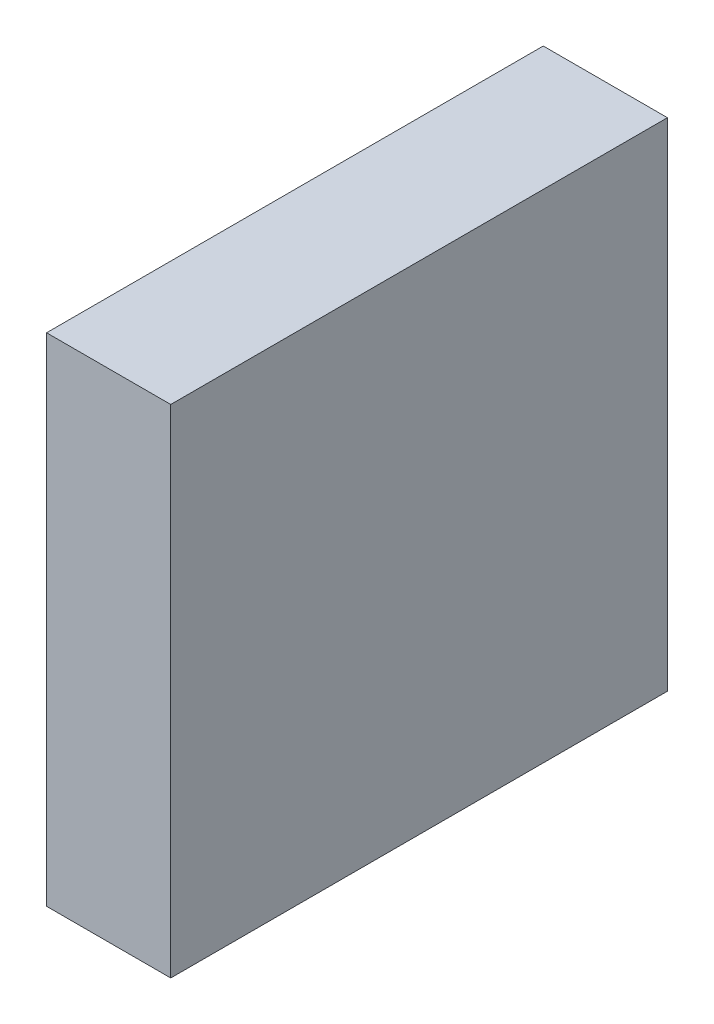
SolidWorks part; units mm, degrees
ref_plane "前视基准面" through (0, 0, 0) normal (0, 0, 1) x (1, 0, 0)
ref_plane "上视基准面" through (0, 0, 0) normal (0, 1, 0) x (1, 0, 0)
ref_plane "右视基准面" through (0, 0, 0) normal (1, 0, 0) x (0, 0, -1)
other "Configuration Table"
sketch "草图1" plane through (0, 0, 0) normal (1, 0, 0) x (0, 0, -1)
  line L1 (0, 0) -> (20, 0)
  line L2 (0, 0) -> (0, 20)
  line L3 (0, 20) -> (20, 20)
  line L4 (20, 0) -> (20, 20)
  dimension "D1" = 20
  dimension "D2" = 20
extrude "凸台-拉伸1" add sketch "草图1" along normal blind 5
